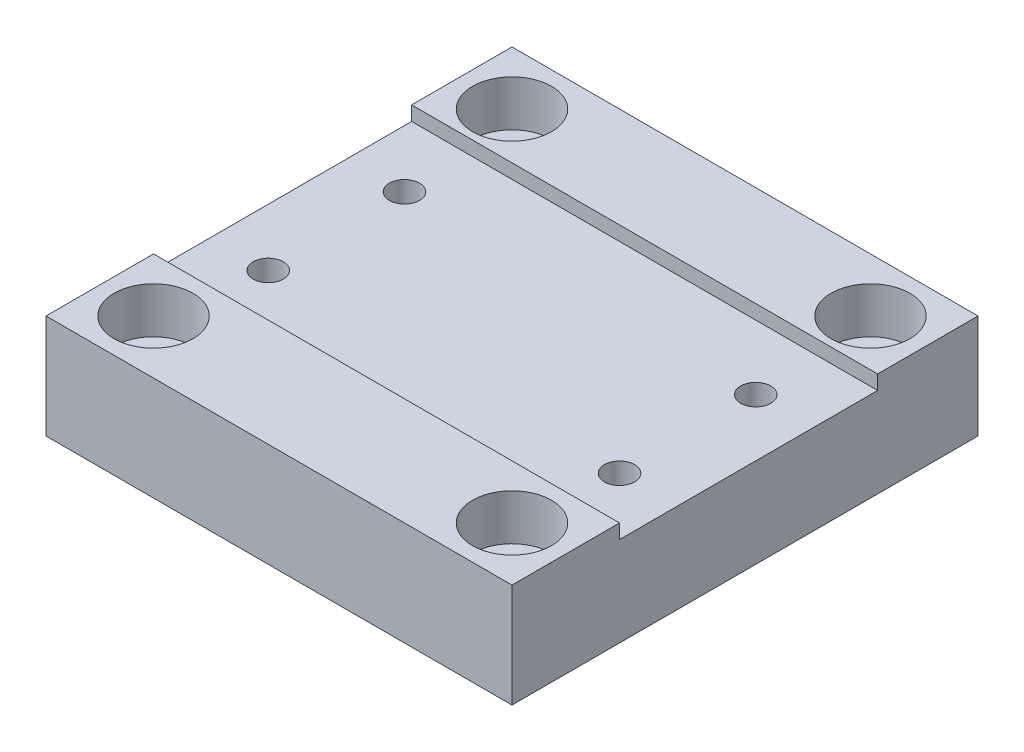
SolidWorks part; units mm, degrees
ref_plane "Ebene vorne" through (0, 0, 0) normal (0, 0, 1) x (1, 0, 0)
ref_plane "Ebene oben" through (0, 0, 0) normal (0, 1, 0) x (1, 0, 0)
ref_plane "Ebene rechts" through (0, 0, 0) normal (1, 0, 0) x (0, 0, -1)
sketch "Skizze1" plane through (0, 0, 0) normal (0, 1, 0) x (1, 0, 0)
  line L1 (-32.5, 32.5) -> (32.5, 32.5)
  line L2 (-32.5, 32.5) -> (-32.5, -32.5)
  line L3 (-32.5, -32.5) -> (32.5, -32.5)
  line L4 (32.5, 32.5) -> (32.5, -32.5)
  point P4 (32.5, 0)
  point P8 (0, -32.5)
  dimension "D1" = 65
  dimension "D2" = 65
extrude "Aufsatz-Linear austragen1" add sketch "Skizze1" along normal blind 14.5
hole_wizard "Stirnsenkung für M6 Zylinderschraube mit Innensechskant1" positions "Skizze2" profile "Skizze3" counterbore size "M6" standard "DIN" end condition through all
sketch "Skizze2" plane through (0, 14.5, 0) normal (0, 1, 0) x (1, 0, 0)
  line L0 (-32.5, -32.5) -> (32.5, -32.5) construction
  line L1 (-32.5, 32.5) -> (-32.5, -32.5) construction
  line L2 (32.5, -32.5) -> (32.5, 32.5) construction
  line L3 (32.5, 32.5) -> (-32.5, 32.5) construction
  point P0 (-25, -25)
  point P2 (-25, 25)
  point P4 (25, 25)
  point P6 (25, -25)
  dimension "D1" = 7.5
  dimension "D2" = 7.5
  dimension "D3" = 7.5
  dimension "D4" = 7.5
  dimension "D5" = 7.5
  dimension "D6" = 7.5
  dimension "D7" = 7.5
  dimension "D8" = 7.5
sketch "Skizze3" plane through (-25, 14.5, 25) normal (1, 0, 0) x (0, 0, 1)
  line L0 (0, 0) -> (0, 14.5)
  line L1 (0, 14.5) -> (3.3, 14.5)
  line L3 (3.3, 14.5) -> (3.3, 6.4)
  line L4 (3.3, 6.4) -> (5.5, 6.4)
  line L5 (5.5, 6.4) -> (5.5, 0)
  line L7 (5.5, 0) -> (0, 0)
  line L11 (0, -6.35) -> (0, 107.95) construction
  dimension "Bohrerdurchmesser" = 6.6
  dimension "Bohrungstiefe" = 14.5
  dimension "Senkdurchmesser2" = 11
  dimension "Senktiefe2" = 6.4
sketch "Skizze8" plane through (0, 14.5, 0) normal (0, 1, 0) x (1, 0, 0)
  line L0 (-32.5, 32.5) -> (-32.5, -32.5) construction
  line L1 (-32.5, -17.5) -> (32.5, -17.5)
  line L2 (-32.5, -17.5) -> (-32.5, 18.5)
  line L3 (-32.5, 18.5) -> (32.5, 18.5)
  line L4 (32.5, -17.5) -> (32.5, 18.5)
  line L5 (32.5, -32.5) -> (32.5, 32.5) construction
  line L6 (-32.5, -32.5) -> (32.5, -32.5) construction
  line L7 (32.5, 32.5) -> (-32.5, 32.5) construction
  dimension "D1" = 15
  dimension "D2" = 14
extrude "Schnitt-Linear austragen1" cut sketch "Skizze8" against normal blind 2
hole_wizard "Kernloch für M5 Gewinde1" positions "Skizze9" profile "Skizze10" hole size "M5" standard "DIN" end condition through all
sketch "Skizze9" plane through (61.7446, 12.5, 78.1259) normal (0, 1, 0) x (0, 0, 1)
  point P0 (-68.6259, -37.2446)
  point P1 (-87.6259, -37.2446)
  point P2 (-87.6259, -86.2446)
  point P3 (-68.6259, -86.2446)
sketch "Skizze10" plane through (24.5, 12.5, 9.5) normal (1, 0, 0) x (0, 0, 1)
  line L0 (0, 0) -> (0, 12.5)
  line L1 (0, 12.5) -> (2.1, 12.5)
  line L2 (2.1, 12.5) -> (2.1, 0)
  line L5 (2.1, 0) -> (0, 0)
  line L11 (0, -6.35) -> (0, 107.95) construction
  dimension "Bohrerdurchmesser" = 4.2
  dimension "Bohrungstiefe" = 12.5
equation "\"31mmmm\"=15"
